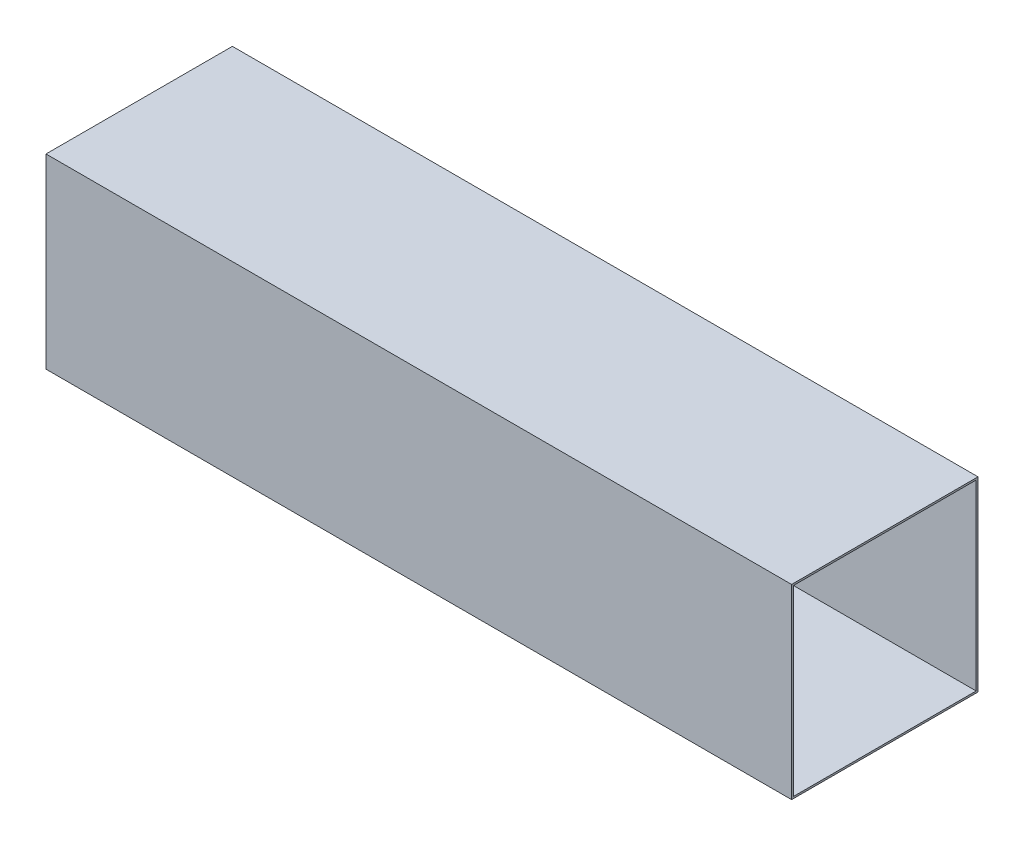
SolidWorks part; units mm, degrees
ref_plane "Ebene vorne" through (0, 0, 0) normal (0, 0, 1) x (1, 0, 0)
ref_plane "Ebene oben" through (0, 0, 0) normal (0, 1, 0) x (1, 0, 0)
ref_plane "Ebene rechts" through (0, 0, 0) normal (1, 0, 0) x (0, 0, -1)
sketch "Sketch1" plane through (0, 0, 0) normal (1, 0, 0) x (0, 0, -1)
  line L1 (0, 0) -> (100, 0)
  line L2 (0, 0) -> (0, 100)
  line L3 (0, 100) -> (100, 100)
  line L4 (100, 0) -> (100, 100)
  line L5 (1, 1) -> (99, 1)
  line L6 (1, 1) -> (1, 99)
  line L7 (1, 99) -> (99, 99)
  line L8 (99, 1) -> (99, 99)
  dimension "D1" = 1
  dimension "D2" = 1
  dimension "D3" = 1
  dimension "D4" = 1
  dimension "D5" = 100
  dimension "D6" = 100
extrude "Boss-Extrude1" add sketch "Sketch1" along normal blind 400
